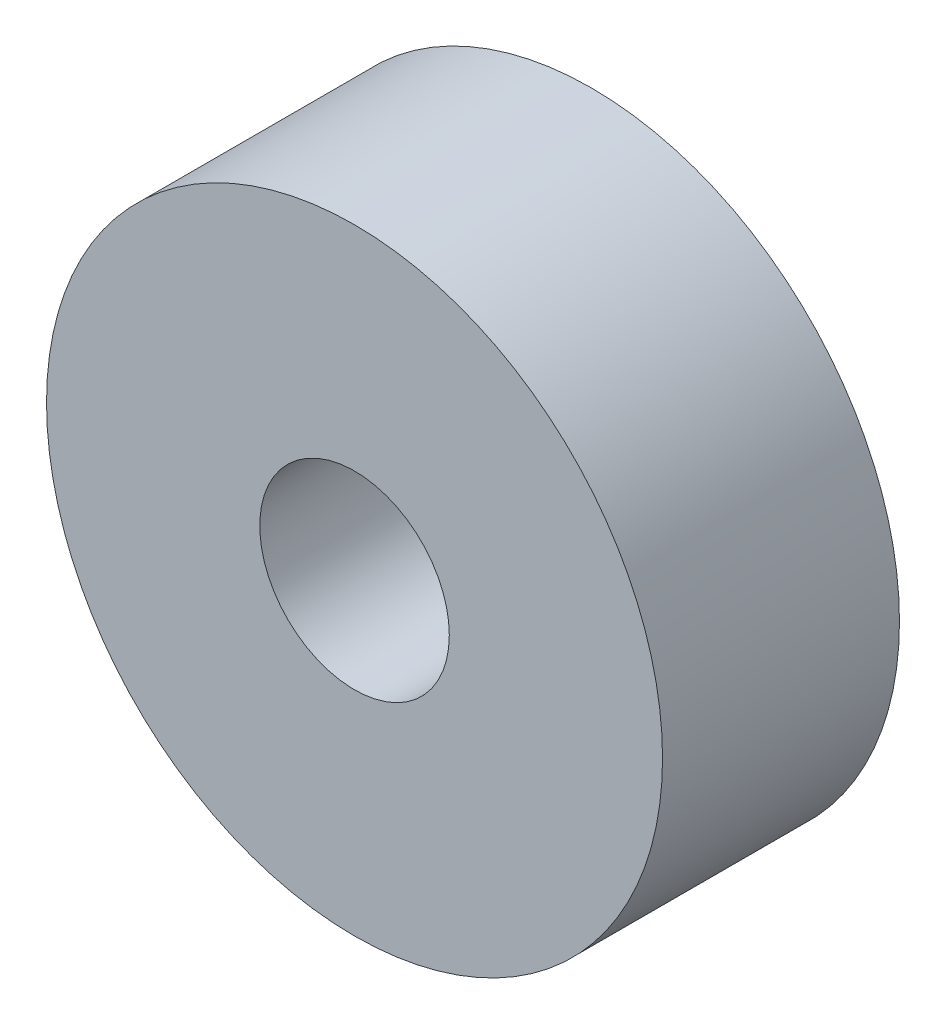
SolidWorks part; units mm, degrees
ref_plane "Спереди" through (0, 0, 0) normal (0, 0, 1) x (1, 0, 0)
ref_plane "Сверху" through (0, 0, 0) normal (0, 1, 0) x (1, 0, 0)
ref_plane "Справа" through (0, 0, 0) normal (1, 0, 0) x (0, 0, -1)
sketch "Эскиз1" plane through (0, 0, 0) normal (0, 0, 1) x (1, 0, 0)
  circle A0 centre (0, 0) radius 6.5
  circle A1 centre (0, 0) radius 2
  dimension "D1" = 4
  dimension "D2" = 13
extrude "Бобышка-Вытянуть1" add sketch "Эскиз1" along normal blind 5
